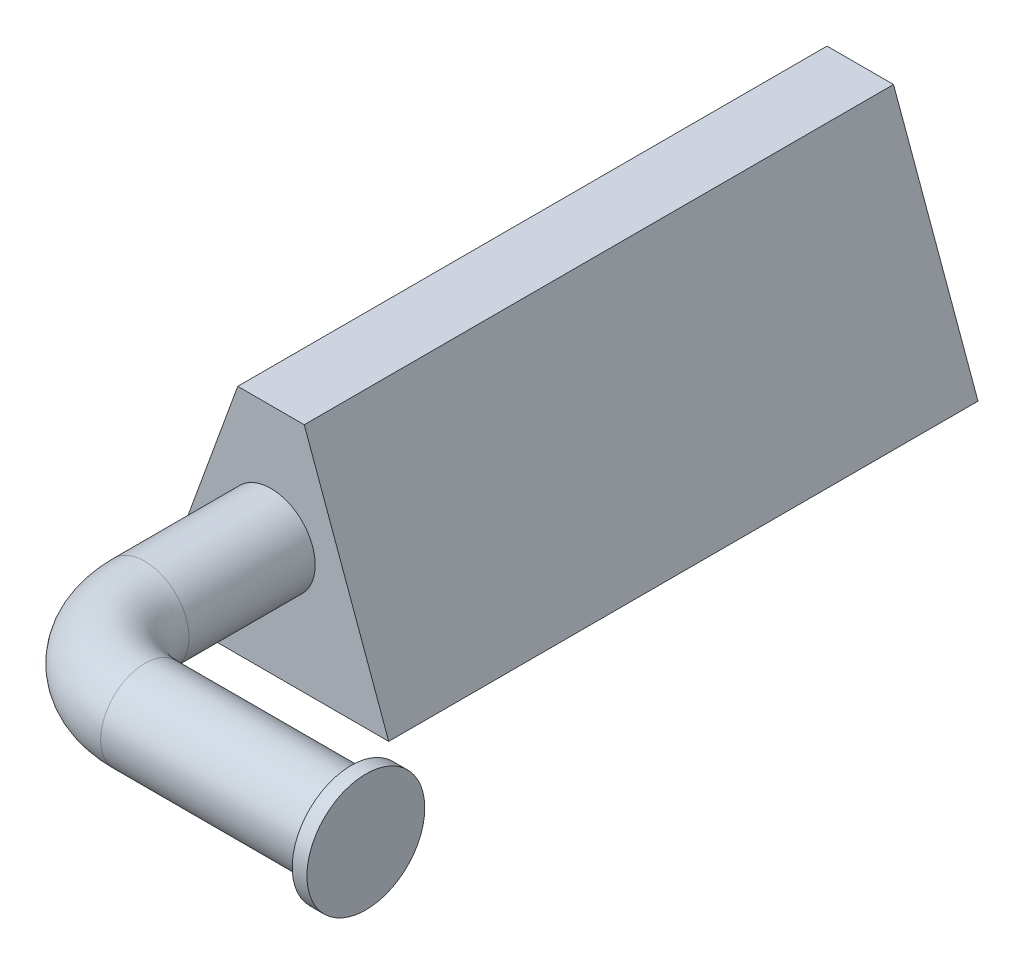
SolidWorks part; units mm, degrees
material "1023 Carbon Steel Sheet (SS)"
ref_plane "Front Plane" through (0, 0, 0) normal (0, 0, 1) x (1, 0, 0)
ref_plane "Top Plane" through (0, 0, 0) normal (0, 1, 0) x (1, 0, 0)
ref_plane "Right Plane" through (0, 0, 0) normal (1, 0, 0) x (0, 0, -1)
sketch "Sketch1" plane through (0, 0, 0) normal (0, 0, 1) x (1, 0, 0)
  line L33 (15.9791, 0) -> (10.2465, 15.75)
  line L34 (10.2465, 15.75) -> (5.7325, 15.75)
  line L35 (5.7325, 15.75) -> (0, 0)
  line L36 (15.9791, 0) -> (0, 0)
  dimension "D2" = 10.2465
  dimension "D3" = 15.75
  dimension "D1" = 5.7325
extrude "Boss-Extrude1" add sketch "Sketch1" along normal blind 40
ref_plane "Plane1" through (0, 7.875, 0) normal (0, -1, 0) x (-1, 0, 0)
sketch "Sketch3" plane through (0, 7.875, 0) normal (0, -1, 0) x (-1, 0, 0)
  line L0 (-7.9895, -40) -> (-7.9895, -48.5622)
  line L1 (0, -40) -> (-15.9791, -40) construction
  line L2 (-13.9895, -54.5622) -> (-27.9895, -54.5622)
  arc A0 (-7.9895, -48.5622) -> (-13.9895, -54.5622) centre (-13.9895, -48.5622) cw
  point P7 (-7.9895, -54.5622)
  dimension "D2" = 6
  dimension "D1" = 20
  dimension "D3" = 8.5622
ref_plane "Plane2" through (27.9895, 0, 0) normal (1, 0, 0) x (0, 0, -1)
sketch "Sketch4" plane through (27.9895, 0, 0) normal (1, 0, 0) x (0, 0, -1)
  line L0 (-40, 7.875) -> (-48.5622, 7.875) construction
  circle A0 centre (-54.5622, 7.875) radius 3
  dimension "D1" = 6
sweep "Sweep1" add profiles "Sketch4" path "Sketch3"
sketch "Sketch5" plane through (27.9895, 0, 0) normal (1, 0, 0) x (0, 0, -1)
  circle A0 centre (-54.5622, 7.875) radius 4
  dimension "D1" = 8
extrude "Boss-Extrude2" add sketch "Sketch5" along normal blind 1
